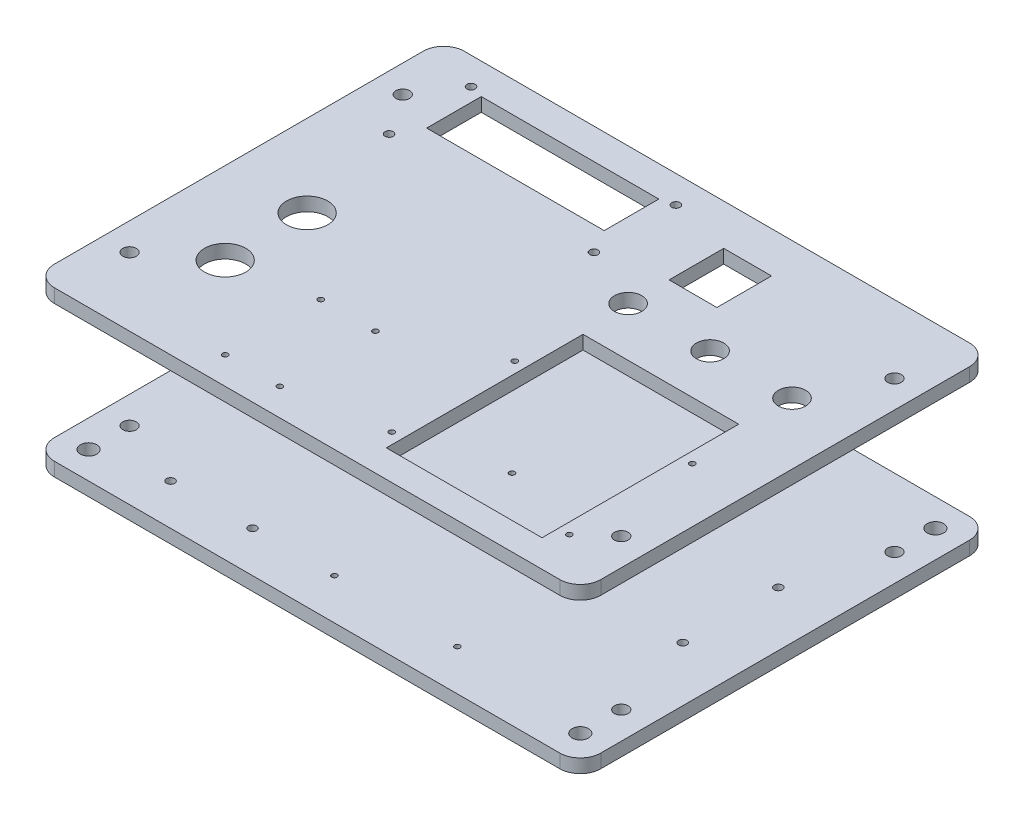
SolidWorks part; units mm, degrees
ref_plane "Front Plane" through (0, 0, 0) normal (0, 0, 1) x (1, 0, 0)
ref_plane "Top Plane" through (0, 0, 0) normal (0, 1, 0) x (1, 0, 0)
ref_plane "Right Plane" through (0, 0, 0) normal (1, 0, 0) x (0, 0, -1)
sketch "Sketch1" plane through (0, 0, 0) normal (0, 1, 0) x (1, 0, 0)
  line L0 (0, -75) -> (200, -75) construction
  line L1 (0, 0) -> (200, 0)
  line L2 (0, 0) -> (0, -150)
  line L3 (0, -150) -> (200, -150)
  line L4 (200, 0) -> (200, -150)
  line L5 (10, -25) -> (190, -25) construction
  line L6 (10, -25) -> (10, -125) construction
  line L7 (10, -125) -> (190, -125) construction
  line L8 (190, -25) -> (190, -125) construction
  line L9 (100, 0) -> (100, -150) construction
  line L11 (10, -10) -> (190, -10) construction
  line L12 (10, -10) -> (10, -140) construction
  line L13 (10, -140) -> (190, -140) construction
  line L14 (190, -10) -> (190, -140) construction
  circle A0 centre (10, -10) radius 3
  circle A1 centre (10, -25) radius 2.5
  circle A2 centre (190, -10) radius 3
  circle A3 centre (190, -25) radius 2.5
  circle A4 centre (190, -140) radius 3
  circle A5 centre (190, -125) radius 2.5
  circle A6 centre (10, -125) radius 2.5
  circle A7 centre (10, -140) radius 3
  point P13 (10, -75)
  point P14 (100, -125)
  point P19 (10, -75)
  point P20 (100, -140)
  dimension "D7" = 6
  dimension "D8" = 5
  dimension "D1" = 150
  dimension "D2" = 200
  dimension "D3" = 10
  dimension "D4" = 25
  dimension "D5" = 10
  dimension "D6" = 10
sketch "Sketch3" plane through (0, 0, 0) normal (0, 0, 1) x (1, 0, 0)
  line L0 (0, 0) -> (200, 0) construction
  line L5 (0, 70) -> (200, 70)
  line L6 (0, 70) -> (0, 65)
  line L7 (0, 65) -> (200, 65)
  line L8 (200, 70) -> (200, 65)
  line L9 (0, 15) -> (200, 15)
  line L10 (0, 15) -> (0, 10)
  line L11 (0, 10) -> (200, 10)
  line L12 (200, 15) -> (200, 10)
  line L13 (0, 0) -> (200, 0)
  point P9 (98.6628, 13.8916)
  point P12 (201.7129, 10)
  point P13 (0, 0)
  point P14 (0, 0)
  dimension "D1" = 10
  dimension "D2" = 5
  dimension "D3" = 50
sketch "Sketch2" plane through (0, 0, 0) normal (0, 1, 0) x (1, 0, 0)
  line L0 (0, 0) -> (200, 0) construction
  line L1 (200, 0) -> (200, -150) construction
  line L2 (0, -150) -> (200, -150) construction
  line L3 (0, 0) -> (0, -150) construction
  line L4 (0, 0) -> (200, 0)
  line L5 (200, 0) -> (200, -150)
  line L6 (0, -150) -> (200, -150)
  line L7 (0, 0) -> (0, -150)
  line L24 (0, -75) -> (200, -75) construction
  line L25 (100, 0) -> (100, -150) construction
  line L26 (0, -75) -> (200, -75) construction
  line L27 (100, 0) -> (100, -150) construction
  line L28 (35, -15) -> (125, -15) construction
  line L29 (35, -75) -> (65, -75) construction
  line L30 (35, -75) -> (35, -135) construction
  line L31 (35, -135) -> (65, -135) construction
  line L32 (65, -75) -> (65, -135) construction
  line L33 (180, -57.5) -> (180, -92.5) construction
  line L35 (95, -70) -> (140, -70) construction
  line L36 (95, -70) -> (95, -135) construction
  line L37 (95, -135) -> (140, -135) construction
  line L38 (140, -70) -> (140, -135) construction
  circle A8 centre (35, -75) radius 1.5
  circle A9 centre (65, -75) radius 1.5
  circle A10 centre (65, -135) radius 1.5
  circle A11 centre (35, -135) radius 1.5
  circle A12 centre (35, -15) radius 1.5
  circle A13 centre (125, -15) radius 1.5
  circle A14 centre (180, -57.5) radius 1.5
  circle A15 centre (180, -92.5) radius 1.5
  circle A16 centre (95, -70) radius 1
  circle A17 centre (140, -70) radius 1
  circle A18 centre (140, -135) radius 1
  circle A19 centre (95, -135) radius 1
  circle A22 centre (190, -25) radius 2.5 construction
  circle A23 centre (190, -10) radius 3 construction
  circle A24 centre (190, -125) radius 2.5 construction
  circle A25 centre (190, -140) radius 3 construction
  circle A26 centre (10, -140) radius 3 construction
  circle A27 centre (10, -125) radius 2.5 construction
  circle A28 centre (10, -25) radius 2.5 construction
  circle A29 centre (10, -10) radius 3 construction
  circle A30 centre (190, -25) radius 2.5
  circle A31 centre (190, -10) radius 3
  circle A32 centre (190, -125) radius 2.5
  circle A33 centre (190, -140) radius 3
  circle A34 centre (10, -140) radius 3
  circle A35 centre (10, -125) radius 2.5
  circle A36 centre (10, -25) radius 2.5
  circle A37 centre (10, -10) radius 3
  point P40 (180, -75)
  dimension "D2" = 35
  dimension "D5" = 3
  dimension "D6" = 3
  dimension "D12" = 3
  dimension "D14" = 2
  dimension "D3" = 60
  dimension "D4" = 30
  dimension "D7" = 90
  dimension "D8" = 15
  dimension "D9" = 35
  dimension "D10" = 15
  dimension "D13" = 20
  dimension "D15" = 65
  dimension "D16" = 45
  dimension "D17" = 30
  dimension "D18" = 40
extrude "Boss-Extrude1" add sketch "Sketch2" along normal up to vertex (15 mm away) from vertex at 10 starting at point (0, 10, 0)
sketch "Sketch4" plane through (0, 0, 0) normal (0, 1, 0) x (1, 0, 0)
  line L0 (30, -80) -> (30, -110) construction
  line L1 (147.5, -89) -> (147.5, -134) construction
  line L2 (20, -10) -> (95, -10) construction
  line L3 (20, -10) -> (20, -40) construction
  line L12 (200, 0) -> (0, 0)
  line L13 (200, -150) -> (200, 0)
  line L14 (0, -150) -> (200, -150)
  line L15 (0, 0) -> (0, -150)
  line L16 (200, 0) -> (0, 0)
  line L17 (200, -150) -> (200, 0)
  line L18 (0, -150) -> (200, -150)
  line L19 (0, 0) -> (0, -150)
  line L20 (20, -40) -> (95, -40) construction
  line L21 (95, -10) -> (95, -40) construction
  line L22 (60, -105) -> (80, -105) construction
  line L23 (60, -105) -> (60, -140) construction
  line L24 (60, -140) -> (80, -140) construction
  line L25 (80, -105) -> (80, -140) construction
  line L26 (115, -89) -> (180, -89) construction
  line L27 (115, -89) -> (115, -134) construction
  line L28 (115, -134) -> (180, -134) construction
  line L29 (180, -89) -> (180, -134) construction
  line L30 (119, -93) -> (176, -93)
  line L31 (119, -93) -> (119, -130)
  line L32 (119, -130) -> (176, -130)
  line L33 (176, -93) -> (176, -130)
  line L34 (180, -111.5) -> (115, -111.5) construction
  line L35 (117.5, -50) -> (177.5, -50) construction
  line L37 (117.5, -15) -> (135, -15)
  line L38 (117.5, -15) -> (117.5, -35)
  line L39 (117.5, -35) -> (135, -35)
  line L40 (135, -15) -> (135, -35)
  line L41 (176, -93) -> (119, -93)
  line L42 (176, -93) -> (176, -68)
  line L43 (176, -68) -> (119, -68)
  line L44 (119, -93) -> (119, -68)
  line L45 (119, -130) -> (176, -130)
  line L46 (119, -130) -> (119, -140)
  line L47 (119, -140) -> (176, -140)
  line L48 (176, -130) -> (176, -140)
  line L53 (25, -11.25) -> (90, -11.25)
  line L54 (25, -11.25) -> (25, -31.25)
  line L55 (25, -31.25) -> (90, -31.25)
  line L56 (90, -11.25) -> (90, -31.25)
  circle A0 centre (30, -80) radius 7.55
  circle A1 centre (60, -105) radius 1
  circle A3 centre (10, -125) radius 2.5
  circle A4 centre (10, -125) radius 2.5
  circle A5 centre (190, -125) radius 2.5
  circle A6 centre (190, -125) radius 2.5
  circle A7 centre (80, -105) radius 1
  circle A9 centre (190, -25) radius 2.5
  circle A10 centre (190, -25) radius 2.5
  circle A11 centre (80, -140) radius 1
  circle A13 centre (10, -25) radius 2.5
  circle A14 centre (10, -25) radius 2.5
  circle A15 centre (60, -140) radius 1
  circle A17 centre (30, -110) radius 7.55
  circle A18 centre (20, -10) radius 1.5
  circle A19 centre (20, -40) radius 1.5
  circle A20 centre (95, -10) radius 1.5
  circle A21 centre (95, -40) radius 1.5
  circle A22 centre (115, -89) radius 1
  circle A23 centre (115, -134) radius 1
  circle A24 centre (180, -134) radius 1
  circle A25 centre (180, -89) radius 1
  circle A26 centre (147.5, -50) radius 5
  circle A27 centre (117.5, -50) radius 5
  circle A28 centre (177.5, -50) radius 5
  point P52 (147.5, -93)
  point P53 (176, -111.5)
  point P58 (147.5, -50)
  point P61 (117.5, -25)
  point P66 (95, -25)
  point P76 (57.5, -11.25)
  point P78 (57.5, -10)
  dimension "D10" = 15.1
  dimension "D14" = 3
  dimension "D2" = 2
  dimension "D20" = 2
  dimension "D26" = 10
  dimension "D11" = 30
  dimension "D12" = 30
  dimension "D13" = 80
  dimension "D15" = 20
  dimension "D16" = 10
  dimension "D17" = 30
  dimension "D18" = 75
  dimension "D5" = 35
  dimension "D7" = 20
  dimension "D9" = 60
  dimension "D19" = 10
  dimension "D21" = 65
  dimension "D22" = 45
  dimension "D23" = 4
  dimension "D24" = 4
  dimension "D25" = 20
  dimension "D27" = 60
  dimension "D28" = 17.5
  dimension "D29" = 20
  dimension "D30" = 25
  dimension "D31" = 50
  dimension "D32" = 10
  dimension "D33" = 5
  dimension "D34" = 2.5
  dimension "D35" = 20
  dimension "D1" = 0
  dimension "D3" = 0
  dimension "D4" = 0
  dimension "D6" = 0
  dimension "D8" = 0
extrude "Boss-Extrude2" add sketch "Sketch4" along normal up to vertex (70 mm away) from vertex at 65 separate body contours L16 L19 L18 L17 A28 A27 A26 A25 A24 A23 A22 A21 A20 A19 A18 A17 A15 A14 A11 A10 A7 A6 A4 A1 A0 L37 L40 L39 L38
fillet "Fillet1" radius 7.5 4 edges at (0, 12.5, 0) (200, 12.5, 0) (200, 12.5, 150) (0, 12.5, 150)
fillet "Fillet2" radius 7.5 4 edges at (200, 67.5, 0) (200, 67.5, 150) (0, 67.5, 0) (0, 67.5, 150)
equation "\"f\"=5"
equation "\"D24@Sketch4\"=\"D23@Sketch4\""
equation "\"D25@Sketch4\"=\"D15@Sketch4\""
